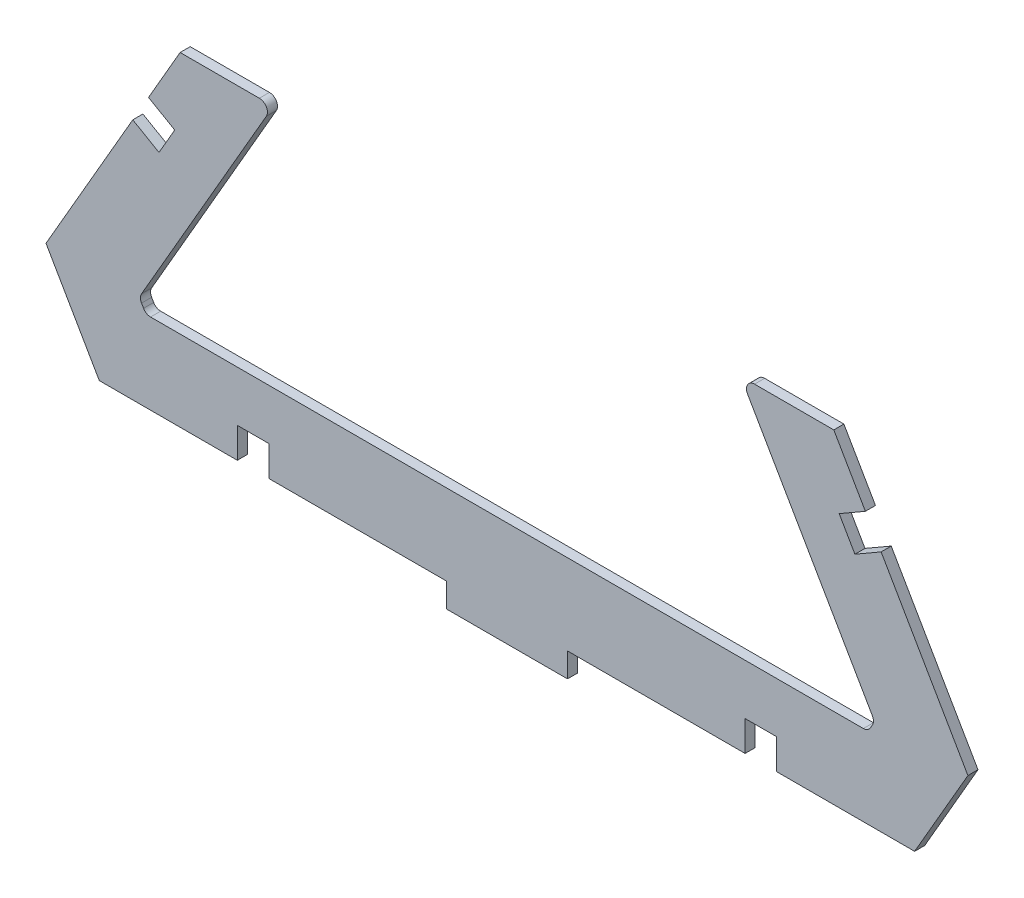
SolidWorks part; units mm, degrees
material "Balsa"
ref_plane "Front Plane" through (0, 0, 0) normal (0, 0, 1) x (1, 0, 0)
ref_plane "Top Plane" through (0, 0, 0) normal (0, 1, 0) x (1, 0, 0)
ref_plane "Right Plane" through (0, 0, 0) normal (1, 0, 0) x (0, 0, -1)
sketch "Sketch1" plane through (0, 0, 0) normal (0, 0, 1) x (1, 0, 0)
  line L0 (0, 0) -> (0, -383.276) construction
  line L1 (0, 0) -> (887.6818, 0) construction
  line L2 (19.05, 0) -> (-19.05, 0)
  line L3 (-19.05, 0) -> (-19.05, 7.62)
  line L4 (-19.05, 7.62) -> (-128.27, 7.62)
  line L5 (-128.27, 7.62) -> (-145.034, 36.6561)
  line L15 (128.27, 7.62) -> (145.034, 36.6561)
  line L16 (19.05, 7.62) -> (128.27, 7.62)
  line L17 (19.05, 0) -> (19.05, 7.62)
  line L18 (-145.034, 36.6561) -> (-95.504, 122.4446)
  line L19 (-95.504, 122.4446) -> (-73.507, 109.7446)
  line L20 (-73.507, 109.7446) -> (-115.7046, 36.6561)
  line L21 (-115.7046, 36.6561) -> (-113.6053, 33.02)
  line L22 (-113.6053, 33.02) -> (113.6053, 33.02)
  line L23 (115.7046, 36.6561) -> (113.6053, 33.02)
  line L24 (73.507, 109.7446) -> (115.7046, 36.6561)
  line L25 (95.504, 122.4446) -> (73.507, 109.7446)
  line L26 (145.034, 36.6561) -> (95.504, 122.4446)
  point P15 (0, 33.02)
  point P20 (0, 0)
  dimension "D2" = 25.4
  dimension "D1" = 60
  dimension "D3" = 25.4
  dimension "D4" = 7.62
  dimension "D5" = 19.05
  dimension "D6" = 109.22
  dimension "D7" = 60
  dimension "D8" = 25.4
  dimension "D9" = 33.528
  dimension "D10" = 99.06
extrude "Boss-Extrude1" add sketch "Sketch1" along normal blind 3.175
sketch "Sketch2" plane through (0, 0, 3.175) normal (0, 0, 1) x (1, 0, 0)
  line L0 (0, 0) -> (0, 33.02) construction
  line L1 (113.6053, 33.02) -> (-113.6053, 33.02) construction
  line L2 (-84.836, 7.62) -> (-84.836, 17.145)
  line L3 (-128.27, 7.62) -> (-19.05, 7.62) construction
  line L4 (-84.836, 17.145) -> (-74.93, 17.145)
  line L5 (-74.93, 17.145) -> (-74.93, 7.62)
  line L6 (-74.93, 7.62) -> (-84.836, 7.62)
  line L7 (-112.776, 92.5286) -> (-104.5271, 87.7661)
  line L8 (-95.504, 122.4446) -> (-145.034, 36.6561) construction
  line L9 (-104.5271, 87.7661) -> (-109.4801, 79.1872)
  line L10 (-109.4801, 79.1872) -> (-117.729, 83.9497)
  line L11 (-117.729, 83.9497) -> (-112.776, 92.5286)
  line L12 (-73.507, 109.7446) -> (-102.8363, 109.7446)
  line L13 (-102.8363, 109.7446) -> (-95.504, 122.4446)
  line L14 (-95.504, 122.4446) -> (-73.507, 109.7446)
  line L15 (95.504, 122.4446) -> (73.507, 109.7446)
  line L16 (102.8363, 109.7446) -> (95.504, 122.4446)
  line L17 (73.507, 109.7446) -> (102.8363, 109.7446)
  line L18 (117.729, 83.9497) -> (112.776, 92.5286)
  line L19 (109.4801, 79.1872) -> (117.729, 83.9497)
  line L20 (104.5271, 87.7661) -> (109.4801, 79.1872)
  line L21 (112.776, 92.5286) -> (104.5271, 87.7661)
  line L22 (74.93, 7.62) -> (84.836, 7.62)
  line L23 (74.93, 17.145) -> (74.93, 7.62)
  line L24 (84.836, 17.145) -> (74.93, 17.145)
  line L25 (84.836, 7.62) -> (84.836, 17.145)
  dimension "D1" = 9.906
  dimension "D2" = 9.525
  dimension "D3" = 74.93
  dimension "D4" = 54.61
extrude "Cut-Extrude1" cut sketch "Sketch2" against normal through all
fillet "Fillet1" radius 2.54 6 edges at (-73.507, 109.7446, 1.5875) (73.507, 109.7446, 1.5875) (113.6053, 33.02, 1.5875) (115.7046, 36.6561, 1.5875) (-113.6053, 33.02, 1.5875) (-115.7046, 36.6561, 1.5875)
